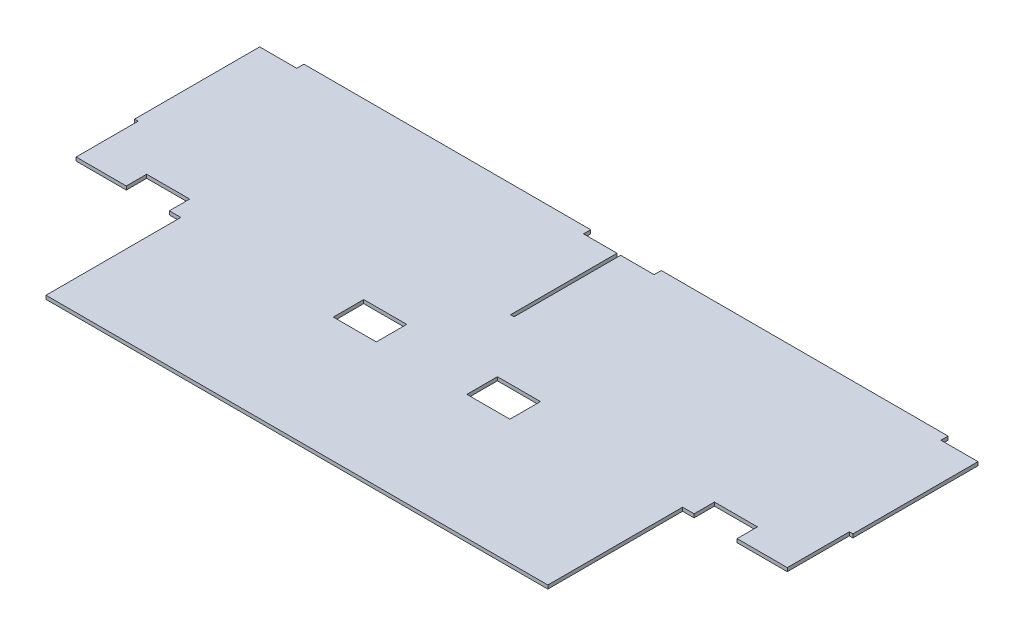
SolidWorks part; units mm, degrees
material "6061-T6 (SS)"
ref_plane "X-Y Datum" through (0, 0, 0) normal (0, 0, 1) x (1, 0, 0)
ref_plane "X-Z Datum" through (0, 0, 0) normal (0, 1, 0) x (1, 0, 0)
ref_plane "Y-Z Datum" through (0, 0, 0) normal (1, 0, 0) x (0, 0, -1)
sketch "Sketch1" plane through (0, 0, 0) normal (0, 1, 0) x (1, 0, 0)
  line L1 (0, 0) -> (629.9098, 0)
  line L2 (0, 0) -> (0, 147.6985)
  line L3 (0, 147.6985) -> (629.9098, 147.6985)
  line L4 (629.9098, 0) -> (629.9098, 147.6985)
extrude "Boss-Extrude1" add sketch "Sketch1" along normal blind 3.175
sketch "Sketch3" plane through (0, 0, -147.6985) normal (0, 0, -1) x (-1, 0, 0)
  line L0 (-629.9098, 0) -> (0, 0) construction
  line L1 (-629.9098, 0) -> (-629.9098, 3.175) construction
  line L2 (-629.9098, 3.175) -> (0, 3.175) construction
  line L3 (0, 0) -> (0, 3.175) construction
  line L4 (-600.2261, 0) -> (-346.2261, 0)
  line L5 (-600.2261, 0) -> (-600.2261, 3.175)
  line L6 (-600.2261, 3.175) -> (-346.2261, 3.175)
  line L7 (-346.2261, 0) -> (-346.2261, 3.175)
  line L8 (-283.6837, 0) -> (-29.6837, 0)
  line L9 (-283.6837, 0) -> (-283.6837, 3.175)
  line L10 (-283.6837, 3.175) -> (-29.6837, 3.175)
  line L11 (-29.6837, 0) -> (-29.6837, 3.175)
extrude "Boss-Extrude2" add sketch "Sketch3" along normal blind 6.35
sketch "Sketch4" plane through (0, 3.175, 0) normal (0, 1, 0) x (1, 0, 0)
  line L0 (346.2261, 147.6985) -> (283.6837, 147.6985) construction
  line L1 (313.3674, 53.332) -> (316.5424, 53.332)
  line L2 (313.3674, 53.332) -> (313.3674, 242.0649)
  line L3 (313.3674, 242.0649) -> (316.5424, 242.0649)
  line L4 (316.5424, 53.332) -> (316.5424, 242.0649)
  line L5 (313.3674, 53.332) -> (316.5424, 242.0649) construction
  line L6 (313.3674, 242.0649) -> (316.5424, 53.332) construction
  point P0 (314.9549, 147.6985)
extrude "Cut-Extrude1" cut sketch "Sketch4" against normal blind 3.175
sketch "Sketch6" plane through (0, 3.175, 0) normal (0, 1, 0) x (1, 0, 0)
  line L0 (314.9549, 53.332) -> (314.9549, 202.815) construction
  line L6 (629.9098, 36.9246) -> (633.0848, 36.9246)
  line L7 (633.0848, 147.6985) -> (633.0848, 36.9246)
  line L8 (629.9098, 147.6985) -> (633.0848, 147.6985)
  line L9 (629.9098, 147.6985) -> (629.9098, 36.9246)
  line L10 (0, 147.6985) -> (0, 36.9246)
  line L11 (0, 147.6985) -> (-3.175, 147.6985)
  line L12 (-3.175, 147.6985) -> (-3.175, 36.9246)
  line L13 (0, 36.9246) -> (-3.175, 36.9246)
extrude "Boss-Extrude4" add sketch "Sketch6" against normal blind 3.175
sketch "Sketch8" plane through (0, 3.175, 0) normal (0, 1, 0) x (1, 0, 0)
  line L1 (0, 0) -> (629.9098, 0)
  line L2 (0, 0) -> (0, -18.0442)
  line L3 (0, -18.0442) -> (629.9098, -18.0442)
  line L4 (629.9098, 0) -> (629.9098, -18.0442)
extrude "Boss-Extrude5" add sketch "Sketch8" against normal through all
sketch "Sketch9" plane through (0, 3.175, 0) normal (0, 1, 0) x (1, 0, 0)
  line L0 (0, -18.0442) -> (47.8104, -18.0442) construction
  line L1 (0, -18.0442) -> (629.9098, -18.0442) construction
  line L2 (314.9549, -18.0442) -> (314.9549, 180.2876) construction
  line L3 (30.0304, -36.0782) -> (65.5904, -36.0782)
  line L4 (30.0304, -36.0782) -> (30.0304, -0.0102)
  line L5 (30.0304, -0.0102) -> (65.5904, -0.0102)
  line L6 (65.5904, -36.0782) -> (65.5904, -0.0102)
  line L7 (30.0304, -36.0782) -> (65.5904, -0.0102) construction
  line L8 (30.0304, -0.0102) -> (65.5904, -36.0782) construction
  line L9 (599.8794, -0.0102) -> (564.3194, -0.0102)
  line L10 (564.3194, -36.0782) -> (564.3194, -0.0102)
  line L11 (599.8794, -36.0782) -> (564.3194, -36.0782)
  line L12 (599.8794, -36.0782) -> (599.8794, -0.0102)
extrude "Cut-Extrude2" [suppressed] cut sketch "Sketch9" against normal through all
sketch "Sketch10" plane through (0, 3.175, 0) normal (0, 1, 0) x (1, 0, 0)
  line L0 (313.3674, 53.332) -> (313.3674, -18.0442) construction
  line L1 (314.9549, -18.0442) -> (314.9549, -25.2417) construction
  line L2 (0, -18.0442) -> (629.9098, -18.0442) construction
  line L3 (313.3674, -18.0442) -> (274.7924, -18.0442) construction
  line L4 (355.1174, 0) -> (393.2174, 0)
  line L5 (274.7924, -18.0442) -> (236.6924, -18.0442)
  line L6 (274.7924, -18.0442) -> (274.7924, 0)
  line L7 (274.7924, 0) -> (236.6924, 0)
  line L8 (236.6924, -18.0442) -> (236.6924, 0)
  line L9 (393.2174, -18.0442) -> (393.2174, 0)
  line L10 (355.1174, -18.0442) -> (393.2174, -18.0442)
  line L11 (355.1174, -18.0442) -> (355.1174, 0)
  line L12 (0, -18.0442) -> (63.5, -18.0442) construction
  line L13 (0, -18.0442) -> (629.9098, -18.0442) construction
  line L22 (585.4598, 0) -> (547.3598, 0)
  line L23 (44.45, -36.0883) -> (82.55, -36.0883)
  line L24 (44.45, -36.0883) -> (44.45, 0)
  line L25 (44.45, 0) -> (82.55, 0)
  line L26 (82.55, -36.0883) -> (82.55, 0)
  line L27 (44.45, -36.0883) -> (82.55, 0) construction
  line L28 (44.45, 0) -> (82.55, -36.0883) construction
  line L29 (547.3598, -36.0883) -> (547.3598, 0)
  line L30 (585.4598, -36.0883) -> (547.3598, -36.0883)
  line L31 (585.4598, -36.0883) -> (585.4598, 0)
  dimension "D1" = 38.575
  dimension "D2" = 38.1
extrude "Cut-Extrude3" cut sketch "Sketch10" against normal through all
sketch "Sketch11" plane through (0, 3.175, 0) normal (0, 1, 0) x (1, 0, 0)
  line L0 (274.7924, -18.0442) -> (355.1174, -18.0442) construction
  line L2 (92.7049, -18.0442) -> (92.7049, -137.4242)
  line L3 (92.7049, -137.4242) -> (537.2049, -137.4242)
  line L4 (537.2049, -18.0442) -> (537.2049, -137.4242)
  line L5 (314.9549, -18.0442) -> (537.2049, -137.4242) construction
  line L6 (92.7049, -137.4242) -> (314.9549, -18.0442) construction
  line L7 (92.7049, -18.0442) -> (236.6924, -18.0442)
  line L8 (274.7924, -18.0442) -> (355.1174, -18.0442)
  line L10 (236.6924, -18.0442) -> (236.6924, -26.9519)
  line L11 (236.6924, -26.9519) -> (274.7924, -26.9519)
  line L12 (274.7924, -18.0442) -> (274.7924, -26.9519)
  line L14 (355.1174, -18.0442) -> (355.1174, -27.0662)
  line L15 (355.1174, -27.0662) -> (393.2174, -27.0662)
  line L16 (393.2174, -18.0442) -> (393.2174, -27.0662)
  line L17 (393.2174, -18.0442) -> (537.2049, -18.0442)
  point P0 (314.9549, -18.0442)
extrude "Boss-Extrude6" add sketch "Sketch11" against normal through all
sketch "Sketch12" [suppressed] plane through (0, 3.175, 0) normal (0, 1, 0) x (1, 0, 0)
  line L1 (44.45, 0) -> (82.55, 0)
  line L2 (44.45, 0) -> (44.45, -18.0442)
  line L3 (44.45, -18.0442) -> (82.55, -18.0442)
  line L4 (82.55, 0) -> (82.55, -18.0442)
  line L5 (547.3598, 0) -> (585.4598, 0)
  line L6 (547.3598, 0) -> (547.3598, -18.0442)
  line L7 (547.3598, -18.0442) -> (585.4598, -18.0442)
  line L8 (585.4598, 0) -> (585.4598, -18.0442)
extrude "Boss-Extrude7" [suppressed] add sketch "Sketch12" against normal through all
